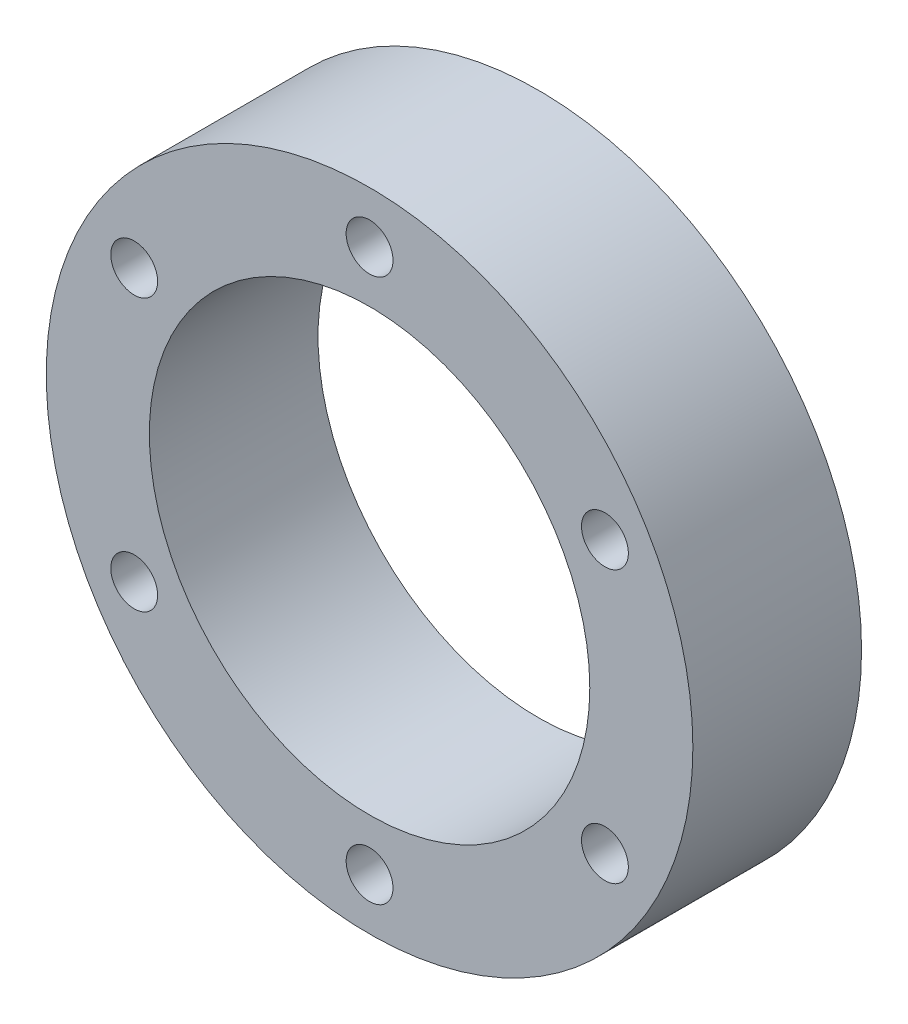
SolidWorks part; units mm, degrees
material "6061-T6 (SS)"
ref_plane "Front Plane" through (0, 0, 0) normal (0, 0, 1) x (1, 0, 0)
ref_plane "Top Plane" through (0, 0, 0) normal (0, 1, 0) x (1, 0, 0)
ref_plane "Right Plane" through (0, 0, 0) normal (1, 0, 0) x (0, 0, -1)
sketch "Sketch1" plane through (0, 0, 0) normal (0, 0, 1) x (1, 0, 0)
  circle A0 centre (0, 0) radius 34.5
  circle A1 centre (0, 0) radius 23.5
  dimension "D1" = 69
  dimension "D2" = 47
extrude "Body" add sketch "Sketch1" along normal blind 18
sketch "Sketch2" plane through (0, 0, 18) normal (0, 0, 1) x (1, 0, 0)
  line L0 (0, 0) -> (0, 34.5) construction
  circle A0 centre (0, 0) radius 34.5 construction
  circle A1 centre (0, 29) radius 2.5
  dimension "D1" = 5
  dimension "D2" = 29
extrude "Bolt Hole" cut sketch "Sketch2" against normal through all
pattern_circular "Bolt Pattern" count 6 over 360 about axis through (0, 0, 0) along (0, 0, 1) of "Bolt Hole"
equation "\"outer_diameter\"= 69.0mm"
equation "\"inner_diameter\"= 47.0mm"
equation "\"spacer_thickness\"= 18.0mm"
equation "\"bolt_diameter\"= 5.0mm"
equation "\"bolt_placement_radius\"= 29.0mm"
equation "\"num_bolts\"= 6.0"
equation "\"D1@Sketch1\"=\"outer_diameter\""
equation "\"D2@Sketch1\"=\"inner_diameter\""
equation "\"D1@Body\" = \"spacer_thickness\""
equation "\"D1@Sketch2\"=\"bolt_diameter\""
equation "\"D2@Sketch2\"=\"bolt_placement_radius\""
equation "\"D1@Bolt Pattern\"=\"num_bolts\""
